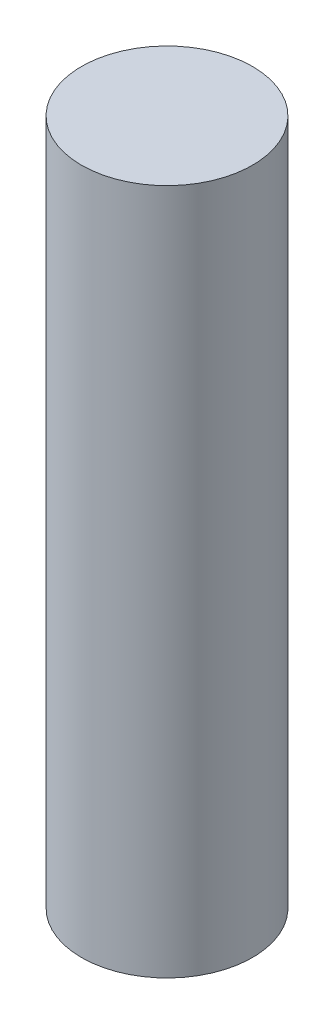
SolidWorks part; units mm, degrees
ref_plane "Front Plane" through (0, 0, 0) normal (0, 0, 1) x (1, 0, 0)
ref_plane "Top Plane" through (0, 0, 0) normal (0, 1, 0) x (1, 0, 0)
ref_plane "Right Plane" through (0, 0, 0) normal (1, 0, 0) x (0, 0, -1)
sketch "Sketch1" plane through (0, 0, 0) normal (0, 1, 0) x (1, 0, 0)
  circle A0 centre (0, 0) radius 0.0935
  dimension "D1" = 0.187
extrude "Boss-Extrude1" add sketch "Sketch1" along normal blind 0.75
